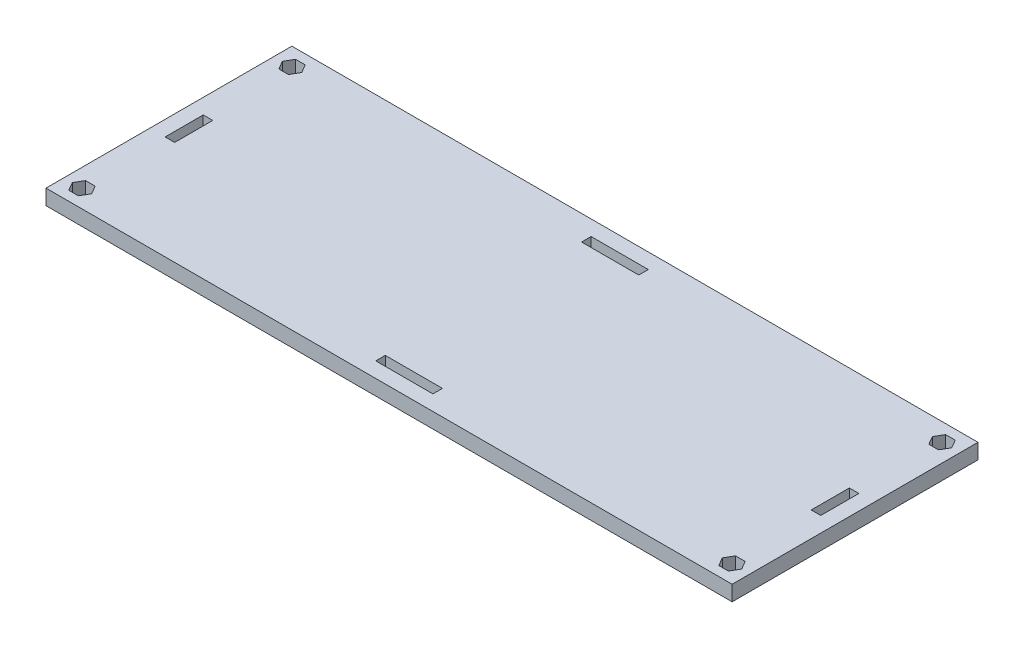
SolidWorks part; units mm, degrees
ref_plane "Alzado" through (0, 0, 0) normal (0, 0, 1) x (1, 0, 0)
ref_plane "Planta" through (0, 0, 0) normal (0, 1, 0) x (1, 0, 0)
ref_plane "Vista lateral" through (0, 0, 0) normal (1, 0, 0) x (0, 0, -1)
sketch "Croquis1" plane through (0, 0, 0) normal (0, 1, 0) x (1, 0, 0)
  line L1 (-90, 32.25) -> (90, 32.25)
  line L2 (-90, 32.25) -> (-90, -32.25)
  line L3 (-90, -32.25) -> (90, -32.25)
  line L4 (90, 32.25) -> (90, -32.25)
  line L5 (-90, 32.25) -> (90, -32.25) construction
  line L6 (-90, -32.25) -> (90, 32.25) construction
  point P0 (0, 0)
  dimension "D1" = 64.5
  dimension "D2" = 180
extrude "Saliente-Extruir1" add sketch "Croquis1" along normal blind 4
sketch "Croquis2" plane through (0, 4, 0) normal (0, 1, 0) x (1, 0, 0)
  line L0 (90, -32.25) -> (90, 32.25) construction
  line L1 (83.5, 5) -> (86, 5)
  line L2 (83.5, 5) -> (83.5, -5)
  line L3 (83.5, -5) -> (86, -5)
  line L4 (86, 5) -> (86, -5)
  line L5 (83.5, 5) -> (86, -5) construction
  line L6 (83.5, -5) -> (86, 5) construction
  point P0 (84.75, 0)
  dimension "D1" = 10
  dimension "D2" = 2.5
  dimension "D3" = 4
extrude "Cortar-Extruir1" cut sketch "Croquis2" against normal up to surface (4 mm away) up to face at (0, 0, 0)
pattern_linear "MatrizL1" count 2 spacing 169.5 along (-1, 0, 0) of "Cortar-Extruir1"
sketch "Croquis3" plane through (0, 0, 0) normal (0, 1, 0) x (1, 0, 0)
  line L0 (90, 32.25) -> (-90, 32.25) construction
  line L1 (-7.5, 28.25) -> (7.5, 28.25)
  line L2 (-7.5, 28.25) -> (-7.5, 25.75)
  line L3 (-7.5, 25.75) -> (7.5, 25.75)
  line L4 (7.5, 28.25) -> (7.5, 25.75)
  line L5 (-7.5, 28.25) -> (7.5, 25.75) construction
  line L6 (-7.5, 25.75) -> (7.5, 28.25) construction
  line L7 (-7.5, -25.75) -> (7.5, -25.75)
  line L8 (-7.5, -28.25) -> (7.5, -28.25)
  line L9 (7.5, -25.75) -> (7.5, -28.25)
  line L10 (-7.5, -25.75) -> (-7.5, -28.25)
  point P0 (0, 27)
  dimension "D1" = 15
  dimension "D2" = 2.5
  dimension "D3" = 4
  dimension "D4" = 2
extrude "Cortar-Extruir2" cut sketch "Croquis3" along normal up to surface (4 mm away) up to face at (-84.75, 4, 0)
sketch "Croquis4" plane through (0, 4, 0) normal (0, 1, 0) x (1, 0, 0)
  line L0 (90, 32.25) -> (-90, 32.25) construction
  line L1 (-82.7193, 27.55) -> (-83.9895, 29.75)
  line L2 (-83.9895, 29.75) -> (-86.5298, 29.75)
  line L3 (-86.5298, 29.75) -> (-87.8, 27.55)
  line L4 (-87.8, 27.55) -> (-86.5298, 25.35)
  line L5 (-86.5298, 25.35) -> (-83.9895, 25.35)
  line L6 (-83.9895, 25.35) -> (-82.7193, 27.55)
  line L7 (-90, 32.25) -> (-90, -32.25) construction
  circle A0 centre (-85.2597, 27.55) radius 2.2 construction
  point P10 (-85.2597, 25.35)
  dimension "D1" = 2.5
  dimension "D2" = 4.4
  dimension "D3" = 2.2
extrude "Cortar-Extruir3" cut sketch "Croquis4" against normal up to surface (4 mm away) up to face at (0, 0, 27)
pattern_linear "MatrizL2" count 2 spacing 170.52 along (1, 0, 0) count 2 spacing 55.1 along (0, 0, 1) of "Cortar-Extruir3"
